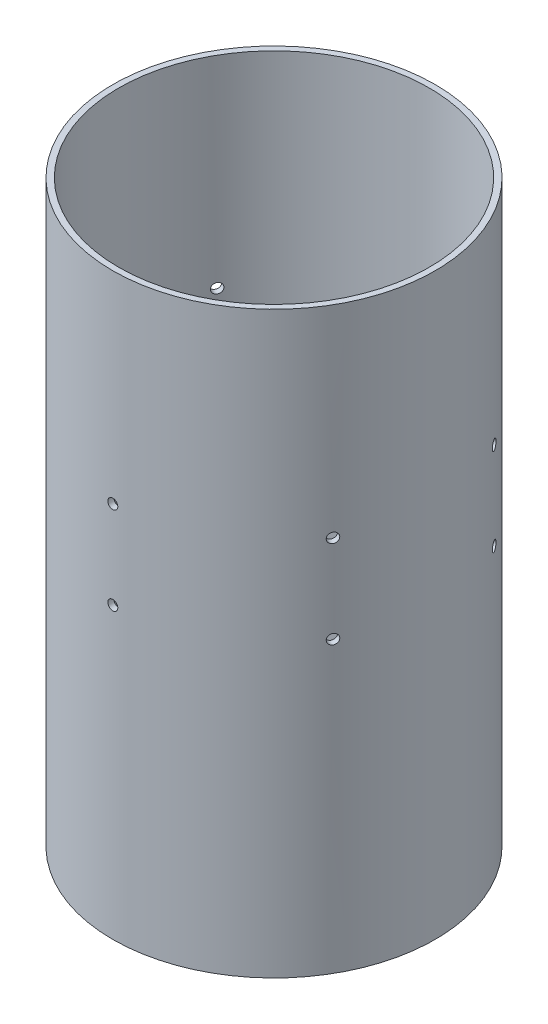
SolidWorks part; units mm, degrees
ref_plane "Front Plane" through (0, 0, 0) normal (0, 0, 1) x (1, 0, 0)
ref_plane "Top Plane" through (0, 0, 0) normal (0, 1, 0) x (1, 0, 0)
ref_plane "Right Plane" through (0, 0, 0) normal (1, 0, 0) x (0, 0, -1)
sketch "Sketch1" plane through (0, 0, 0) normal (0, 1, 0) x (1, 0, 0)
  circle A0 centre (0, 0) radius 47.6885
  circle A1 centre (0, 0) radius 49.5046
  dimension "D1" = 99.0092
  dimension "D2" = 95.377
extrude "Boss-Extrude1" add sketch "Sketch1" along normal blind 177.8
sketch "Sketch2" plane through (0, 0, 0) normal (0, 0, 1) x (1, 0, 0)
  line L0 (0, 177.8) -> (0, 117.348)
  line L1 (49.5046, 177.8) -> (-49.5046, 177.8) construction
  line L2 (0, 117.348) -> (0, 115.824)
  circle A0 centre (0, 115.824) radius 1.524
  dimension "D2" = 3.048
  dimension "D1" = 60.452
extrude "Cut-Extrude1" cut sketch "Sketch2" against normal blind 177.8
pattern_circular "CirPattern1" count 6 over 360 about axis through (0, 177.8, 0) along (0, -1, 0) of "Cut-Extrude1"
sketch "Sketch3" plane through (0, 0, 0) normal (0, 0, 1) x (1, 0, 0)
  line L0 (0, 0) -> (0, 87.376)
  line L1 (-49.5046, 0) -> (49.5046, 0) construction
  line L2 (0, 87.376) -> (0, 88.9)
  circle A0 centre (0, 88.9) radius 1.524
  dimension "D2" = 3.048
  dimension "D1" = 87.376
extrude "Cut-Extrude2" cut sketch "Sketch3" against normal blind 177.8
pattern_circular "CirPattern2" count 6 over 360 about axis through (0, 177.8, 0) along (0, -1, 0) of "Cut-Extrude2"
